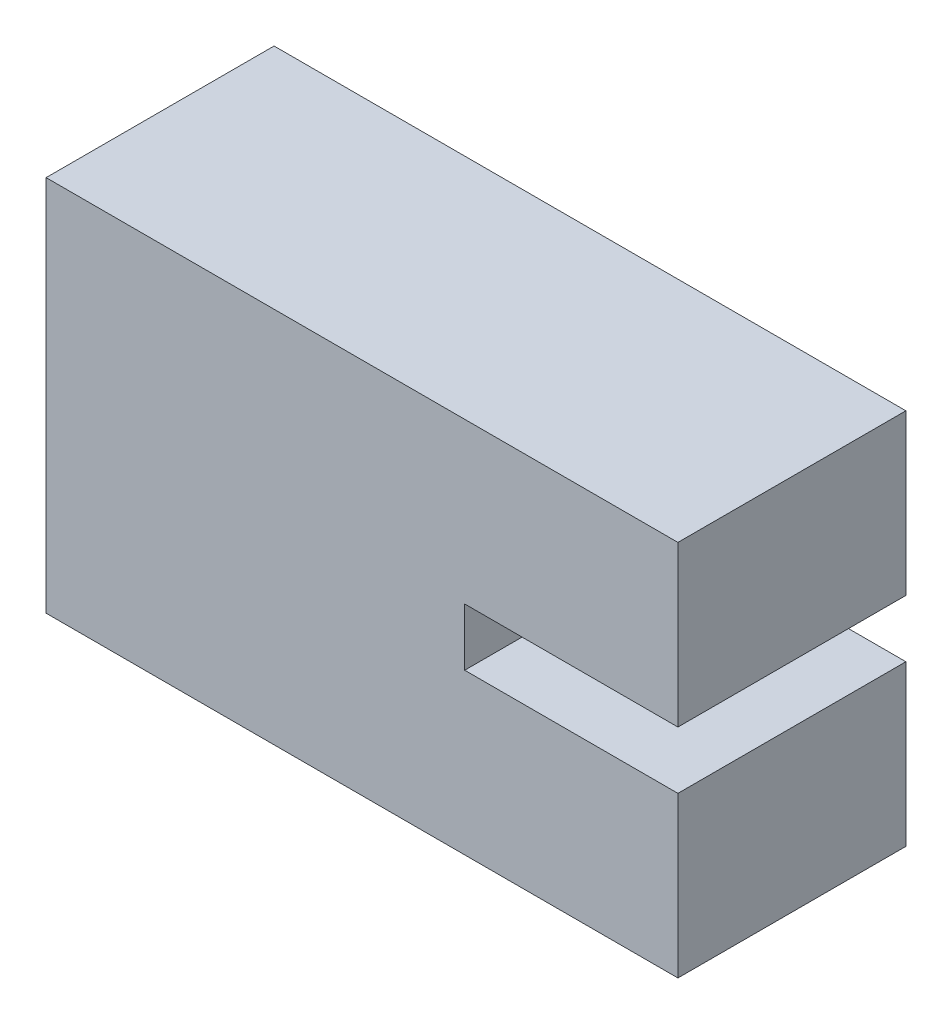
SolidWorks part; units mm, degrees
ref_plane "Front Plane" through (0, 0, 0) normal (0, 0, 1) x (1, 0, 0)
ref_plane "Top Plane" through (0, 0, 0) normal (0, 1, 0) x (1, 0, 0)
ref_plane "Right Plane" through (0, 0, 0) normal (1, 0, 0) x (0, 0, -1)
sketch "Sketch1" plane through (0, 0, 0) normal (0, 0, 1) x (1, 0, 0)
  line L0 (0, 0) -> (0, 14.1537)
  line L1 (0, 14.1537) -> (19.7046, 14.1537)
  line L2 (19.7046, 14.1537) -> (19.7046, 8.1537)
  line L3 (19.7046, 8.1537) -> (11.7046, 8.1537)
  line L4 (11.7046, 8.1537) -> (11.7046, 6)
  line L5 (11.7046, 6) -> (19.7046, 6)
  line L6 (19.7046, 6) -> (19.7046, 0)
  line L7 (19.7046, 0) -> (0, 0)
  dimension "D1" = 8
  dimension "D2" = 2.1537
  dimension "D3" = 6
extrude "Boss-Extrude1" add sketch "Sketch1" along normal blind 8.553
sketch "Sketch2" plane through (0, 0, 0) normal (-1, 0, 0) x (0, 0, 1)
  line L1 (0, 14.1537) -> (8.553, 14.1537)
  line L2 (0, 14.1537) -> (0, 0)
  line L3 (0, 0) -> (8.553, 0)
  line L4 (8.553, 14.1537) -> (8.553, 0)
extrude "Boss-Extrude2" add sketch "Sketch2" along normal blind 4
